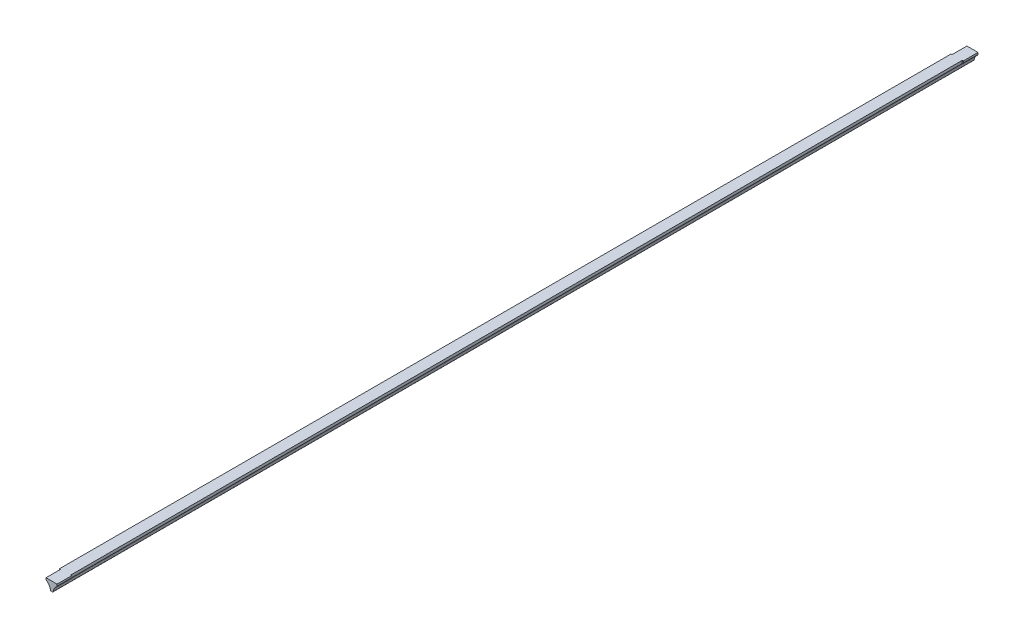
SolidWorks part; units mm, degrees
material "1060 Alloy"
ref_plane "Front Plane" through (0, 0, 0) normal (0, 0, 1) x (1, 0, 0)
ref_plane "Top Plane" through (0, 0, 0) normal (0, 1, 0) x (1, 0, 0)
ref_plane "Right Plane" through (0, 0, 0) normal (1, 0, 0) x (0, 0, -1)
sketch "Sketch1" plane through (0, 0, 0) normal (0, 0, 1) x (1, 0, 0)
  line L10 (-2.8692, 3.0685) -> (2.8692, 3.0685)
  line L11 (2.8692, 3.0685) -> (2.8692, 1.8721)
  line L12 (-2.8692, 3.0685) -> (-3.7066, 3.0685)
  line L13 (-3.7066, 3.0685) -> (-3.7066, 2.3122)
  arc A0 (2.8692, 1.8721) -> (1.9636, 1.0919) centre (5.4739, -2.0668) ccw
  arc A1 (1.9636, 1.0919) -> (0.796, -1.4211) centre (5.4739, -2.0668) ccw
  arc A2 (-0.796, -1.4211) -> (-1.9636, 1.0919) centre (-5.4739, -2.0668) ccw
  arc A3 (0.2713, -1.872) -> (-0.2713, -1.872) centre (0, -21.4602) ccw
  arc A4 (0.2713, -1.872) -> (0.796, -1.4211) centre (0.2785, -1.3497) ccw
  arc A5 (-0.796, -1.4211) -> (-0.2713, -1.872) centre (-0.2785, -1.3497) ccw
  arc A6 (-1.9636, 1.0919) -> (-3.7066, 2.3122) centre (-5.4739, -2.0668) ccw
  arc A7 (2.8692, 1.8721) -> (1.9636, 1.0919) centre (5.4739, -2.0668) ccw
  arc A8 (1.9636, 1.0919) -> (0.796, -1.4211) centre (5.4739, -2.0668) ccw
  arc A9 (-0.796, -1.4211) -> (-1.9636, 1.0919) centre (-5.4739, -2.0668) ccw
  arc A10 (0.2713, -1.872) -> (-0.2713, -1.872) centre (0, -21.4602) ccw
  arc A11 (0.2713, -1.872) -> (0.796, -1.4211) centre (0.2785, -1.3497) ccw
  arc A12 (-0.796, -1.4211) -> (-0.2713, -1.872) centre (-0.2785, -1.3497) ccw
  arc A13 (-1.9636, 1.0919) -> (-2.8692, 1.8721) centre (-5.4739, -2.0668) ccw
  circle A118 centre (-3.4388, 2.465) radius 0.1258
  circle A119 centre (2.6192, 2.5685) radius 0.1393
  dimension "D3" = 0.5
  dimension "D5" = 0.25
extrude "Boss-Extrude1" add sketch "Sketch1" along normal mid plane 500 contours A6 A2 A5 A3 A4 A1 A0 L11 L10 L12 L13 A119 A118
sketch "Sketch9" plane through (0, 0, 0) normal (0, 0, 1) x (1, 0, 0)
  line L1 (2.8692, 3.0685) -> (2.3111, 3.0685)
  line L2 (2.8692, 3.0685) -> (2.8692, 1.2498)
  line L3 (2.8692, 1.2498) -> (2.3111, 1.2498)
  line L4 (2.3111, 3.0685) -> (2.3111, 1.2498)
  dimension "D1" = 0.5581
extrude "Cut-Extrude6" cut sketch "Sketch9" along normal offset from surface 8 and the other way offset from surface (242 mm away) 8 contours L2 L3 L4 L1 up to face at (-0.191, 0.5191, 250) other way up to face at (-0.191, 0.5191, -250)
sketch "Sketch10" plane through (0, 0, 0) normal (0, 0, 1) x (1, 0, 0)
  line L0 (-3.1484, 3.0685) -> (-3.7066, 3.0685)
  line L1 (-3.1484, 3.0685) -> (-3.1484, 2.0431)
  line L3 (-3.7066, 3.0685) -> (-3.7066, 2.3122)
  circle A0 centre (-3.4388, 2.465) radius 0.1258 construction
  circle A1 centre (-3.4388, 2.465) radius 0.1258
  arc A2 (-1.9636, 1.0919) -> (-3.7066, 2.3122) centre (-5.4739, -2.0668) ccw construction
  arc A3 (-3.1484, 2.0431) -> (-3.7066, 2.3122) centre (-5.4739, -2.0668) ccw
sketch "Sketch11" plane through (0, 0, 242) normal (0, 0, -1) x (-1, 0, 0)
  line L0 (3.7066, 3.0685) -> (3.7066, 2.3122) construction
  line L1 (2.8692, 3.0685) -> (3.7066, 3.0685) construction
  line L2 (3.1484, 3.0685) -> (3.1484, 2.0431) construction
  line L3 (3.7066, 3.0685) -> (3.7066, 2.3122)
  line L4 (3.1484, 3.0685) -> (3.7066, 3.0685)
  line L5 (3.1484, 3.0685) -> (3.1484, 2.0431)
  arc A0 (3.7066, 2.3122) -> (1.9636, 1.0919) centre (5.4739, -2.0668) ccw construction
  circle A1 centre (3.4388, 2.465) radius 0.1258 construction
  arc A2 (3.7066, 2.3122) -> (3.1484, 2.0431) centre (5.4739, -2.0668) ccw
  circle A3 centre (3.4388, 2.465) radius 0.1258
  circle A4 centre (-2.6192, 2.5685) radius 0.1393 construction
  circle A5 centre (-2.6192, 2.5685) radius 0.1393
extrude "Cut-Extrude7" cut sketch "Sketch11" against normal blind 8
sketch "Sketch13" plane through (0, 0, 250) normal (0, 0, 1) x (1, 0, 0)
  circle A1 centre (-3.4388, 2.465) radius 0.1258
  circle A2 centre (-3.4388, 2.465) radius 0.1258
  dimension "D1" = 0
extrude "Cut-Extrude12" cut sketch "Sketch13" against normal blind 1
mirror "Mirror1" about plane through (0, 0, 0) normal (0, 0, 1) of "Cut-Extrude7", "Cut-Extrude12"
fillet "Fillet3" radius 0.5 6 edges at (2.8692, 1.8721, -246) (2.8692, 1.8721, 246) (-3.7066, 2.3122, 0) (2.3111, 1.4398, 0) (-3.1484, 2.0431, -246) (-3.1484, 2.0431, 246)
